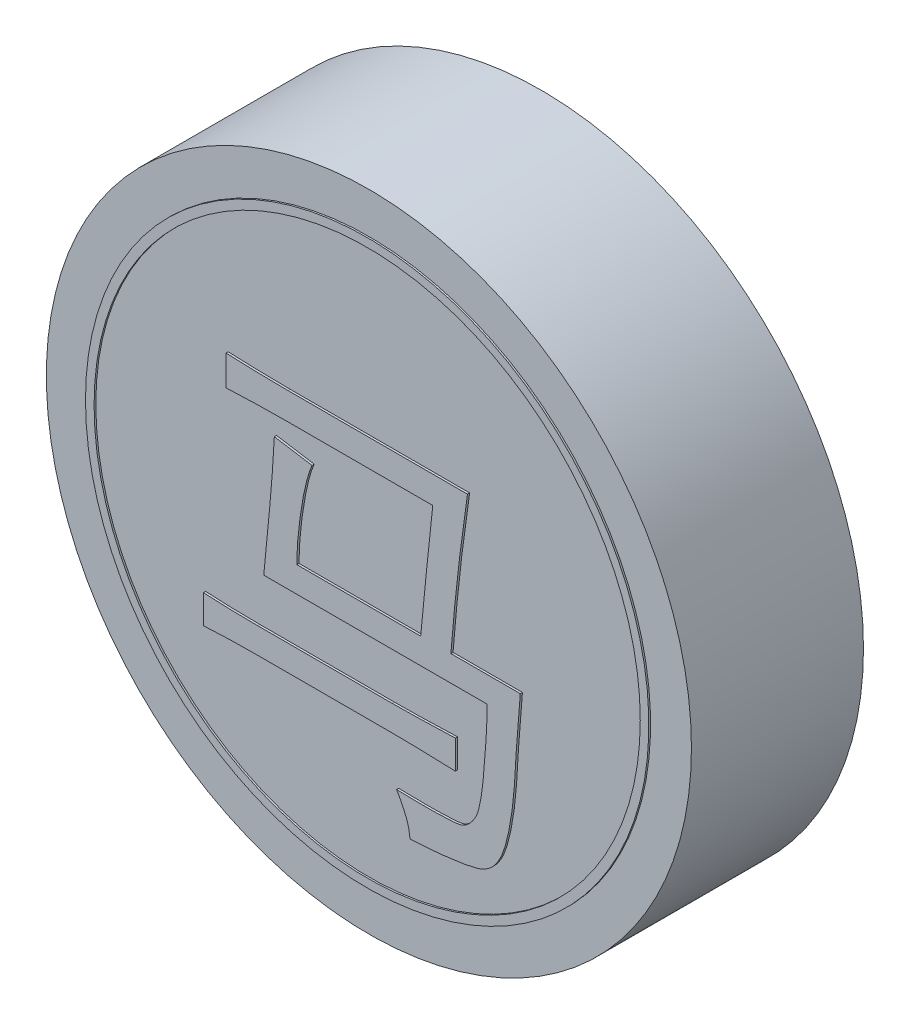
SolidWorks part; units mm, degrees
ref_plane "前视基准面" through (0, 0, 0) normal (0, 0, 1) x (1, 0, 0)
ref_plane "上视基准面" through (0, 0, 0) normal (0, 1, 0) x (1, 0, 0)
ref_plane "右视基准面" through (0, 0, 0) normal (1, 0, 0) x (0, 0, -1)
other "Configuration Table"
sketch "草图1" plane through (0, 0, 0) normal (0, 0, 1) x (1, 0, 0)
  circle A0 centre (0, 0) radius 15
  dimension "D1" = 30
extrude "Diameter30_Height8" add sketch "草图1" against normal blind 8
sketch "草图2" plane through (0, 0, 0) normal (0, 0, 1) x (1, 0, 0)
  text T0 "马" font "SimHei" height 12
extrude "Character_马" add sketch "草图2" along normal blind 0.1
sketch "草图3" plane through (0, 0, 0) normal (0, 0, 1) x (1, 0, 0)
  circle A0 centre (0, 0) radius 13.1
  circle A1 centre (0, 0) radius 12.7
extrude "Ink_ring" add sketch "草图3" along normal blind 0.08
